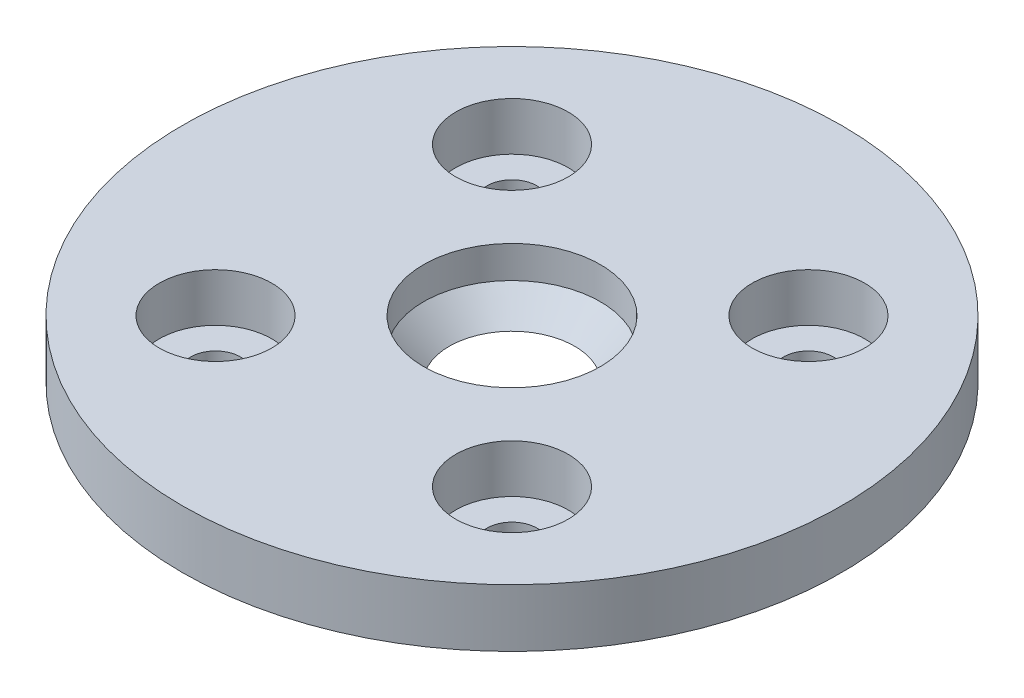
SolidWorks part; units mm, degrees
ref_plane "Front Plane" through (0, 0, 0) normal (0, 0, 1) x (1, 0, 0)
ref_plane "Top Plane" through (0, 0, 0) normal (0, 1, 0) x (1, 0, 0)
ref_plane "Right Plane" through (0, 0, 0) normal (1, 0, 0) x (0, 0, -1)
sketch "Sketch1" plane through (0, 0, 0) normal (0, 1, 0) x (1, 0, 0)
  circle A0 centre (0, 0) radius 10.25
  dimension "D1" = 20.5
extrude "Boss-Extrude1" add sketch "Sketch1" along normal blind 0.8
sketch "Sketch2" plane through (0, 0.8, 0) normal (0, 1, 0) x (1, 0, 0)
  line L0 (0, 0) -> (4.6103, 4.6103) construction
  line L1 (0, 0) -> (-4.6103, -4.6103) construction
  line L2 (-4.6103, -4.6103) -> (-4.6103, 4.6103) construction
  line L3 (4.6103, 4.6103) -> (-4.6103, 4.6103) construction
  line L4 (4.6103, 4.6103) -> (4.6103, -4.6103) construction
  line L5 (-4.6103, -4.6103) -> (4.6103, -4.6103) construction
  circle A0 centre (0, 0) radius 8 construction
  circle A2 centre (-4.6103, -4.6103) radius 1.75
  circle A3 centre (4.6103, 4.6103) radius 1.75
  circle A4 centre (4.6103, -4.6103) radius 1.75
  circle A5 centre (-4.6103, 4.6103) radius 1.75
  dimension "D1" = 16
  dimension "D2" = 6.52
  dimension "D4" = 3.5
  dimension "D5" = 3.5
  dimension "D3" = 6.52
hole_wizard "CSK for M2.5 Flat Head Machine Screw1" positions "Sketch3" profile "Sketch4" countersink size "M2.5" standard "ANSI Metric"
sketch "Sketch3" plane through (0, 0.8, 0) normal (0, 1, 0) x (1, 0, 0)
  point P0 (0, 0)
sketch "Sketch4" plane through (0, 0.8, 0) normal (1, 0, 0) x (0, 0, 1)
  line L0 (0, 0) -> (0, 15.8712)
  line L1 (0, 15.8712) -> (1.45, 15)
  line L2 (1.45, 15) -> (1.45, 1.3)
  line L3 (1.45, 1.3) -> (2.75, 0)
  line L5 (2.75, 0) -> (0, 0)
  line L6 (-1.45, 1.3) -> (-2.75, 0) construction
  line L10 (0, 15.8712) -> (-1.45, 15) construction
  line L11 (0, -6.35) -> (0, 107.95) construction
  dimension "Hole Dia." = 2.9
  dimension "Hole Depth" = 15
  dimension "Near C'Sink Dia." = 5.5
  dimension "Near C'Sink Angle" = 90
  dimension "Drill Angle" = 118
extrude "Cut-Extrude1" cut sketch "Sketch2" against normal blind 0.5
sketch "Sketch5" plane through (0, 0.3, 0) normal (0, 1, 0) x (1, 0, 0)
  circle A0 centre (-4.6103, -4.6103) radius 0.775
  circle A1 centre (4.6103, 4.6103) radius 0.775
  circle A2 centre (4.6103, -4.6103) radius 0.775
  circle A3 centre (-4.6103, 4.6103) radius 0.775
  dimension "D1" = 1.55
  dimension "D2" = 1.55
extrude "Cut-Extrude2" cut sketch "Sketch5" against normal blind 0.5
sketch "Sketch6" plane through (0, 0.8, 0) normal (0, 1, 0) x (1, 0, 0)
  circle A0 centre (4.6103, 4.6103) radius 1.75 construction
  circle A1 centre (0, 0) radius 2.75 construction
  circle A2 centre (0, 0) radius 10.25 construction
  circle A3 centre (-4.6103, -4.6103) radius 1.75 construction
  circle A4 centre (4.6103, 4.6103) radius 1.75
  circle A5 centre (0, 0) radius 2.75
  circle A6 centre (0, 0) radius 10.25
  circle A7 centre (-4.6103, -4.6103) radius 1.75
  circle A8 centre (4.6103, -4.6103) radius 1.75
  circle A9 centre (-4.6103, 4.6103) radius 1.75
extrude "Boss-Extrude2" add sketch "Sketch6" along normal blind 1
sketch "Sketch12" plane through (0, 0, 0) normal (0, -1, 0) x (1, 0, 0)
  line L0 (-3.2144, 7.853) -> (-2.2577, 5.5433)
  line L1 (2.3345, 5.5433) -> (3.2912, 7.853)
  line L2 (-5.5049, 2.2961) -> (-7.8146, 3.2528)
  line L3 (-7.8146, -3.2528) -> (-5.5049, -2.2961)
  line L4 (-2.2577, -5.5433) -> (-3.2144, -7.853)
  line L5 (3.2912, -7.853) -> (2.3345, -5.5433)
  line L6 (7.8914, 3.2528) -> (5.5817, 2.2961)
  line L7 (5.5817, -2.2961) -> (7.8914, -3.2528)
  arc A0 (3.2912, 7.853) -> (-3.2144, 7.853) centre (0.0384, 0) ccw
  arc A1 (2.3345, 5.5433) -> (-2.2577, 5.5433) centre (0.0384, 0) ccw
  arc A2 (-5.5049, 2.2961) -> (-5.5049, -2.2961) centre (0.0384, 0) ccw
  arc A3 (-7.8146, 3.2528) -> (-7.8146, -3.2528) centre (0.0384, 0) ccw
  arc A4 (-2.2577, -5.5433) -> (2.3345, -5.5433) centre (0.0384, 0) ccw
  arc A5 (-3.2144, -7.853) -> (3.2912, -7.853) centre (0.0384, 0) ccw
  arc A6 (7.8914, -3.2528) -> (7.8914, 3.2528) centre (0.0384, 0) ccw
  arc A7 (5.5817, -2.2961) -> (5.5817, 2.2961) centre (0.0384, 0) ccw
extrude "Cut-Extrude3" cut sketch "Sketch12" against normal blind 1
sketch "Sketch13" plane through (0, 0, 0) normal (0, -1, 0) x (-1, 0, 0)
  line L0 (2.3244, 4.9847) -> (3.8036, 8.1568)
  line L1 (-2.3244, 4.9847) -> (-3.8036, 8.1568)
  line L2 (4.9847, 2.3244) -> (8.1568, 3.8036)
  line L3 (4.9847, -2.3244) -> (8.1568, -3.8036)
  line L4 (2.3244, -4.9847) -> (3.8036, -8.1568)
  line L5 (-2.3244, -4.9847) -> (-3.8036, -8.1568)
  line L6 (-4.9847, -2.3244) -> (-8.1568, -3.8036)
  line L7 (-4.9847, 2.3244) -> (-8.1568, 3.8036)
  line L8 (-3.2912, 7.853) -> (-2.3345, 5.5433) construction
  line L9 (2.2577, 5.5433) -> (3.2144, 7.853) construction
  line L10 (7.8146, 3.2528) -> (5.5049, 2.2961) construction
  line L11 (5.5049, -2.2961) -> (7.8146, -3.2528) construction
  line L12 (3.2144, -7.853) -> (2.2577, -5.5433) construction
  line L13 (-2.3345, -5.5433) -> (-3.2912, -7.853) construction
  line L14 (-7.8914, -3.2528) -> (-5.5817, -2.2961) construction
  line L15 (-5.5817, 2.2961) -> (-7.8914, 3.2528) construction
  arc A0 (2.3244, 4.9847) -> (-2.3244, 4.9847) centre (0, 0) ccw
  arc A1 (3.8036, 8.1568) -> (-3.8036, 8.1568) centre (0, 0) ccw
  arc A2 (8.1568, -3.8036) -> (8.1568, 3.8036) centre (0, 0) ccw
  arc A3 (4.9847, -2.3244) -> (4.9847, 2.3244) centre (0, 0) ccw
  arc A4 (-3.8036, -8.1568) -> (3.8036, -8.1568) centre (0, 0) ccw
  arc A5 (-2.3244, -4.9847) -> (2.3244, -4.9847) centre (0, 0) ccw
  arc A6 (-8.1568, 3.8036) -> (-8.1568, -3.8036) centre (0, 0) ccw
  arc A7 (-4.9847, 2.3244) -> (-4.9847, -2.3244) centre (0, 0) ccw
  dimension "D1" = 2.5
  dimension "D2" = 2.5
  dimension "D3" = 2.5
  dimension "D4" = 2.5
  dimension "D5" = 2.5
  dimension "D6" = 2.5
  dimension "D7" = 2.5
  dimension "D8" = 2.5
extrude "Cut-Extrude4" cut sketch "Sketch13" against normal blind 1
